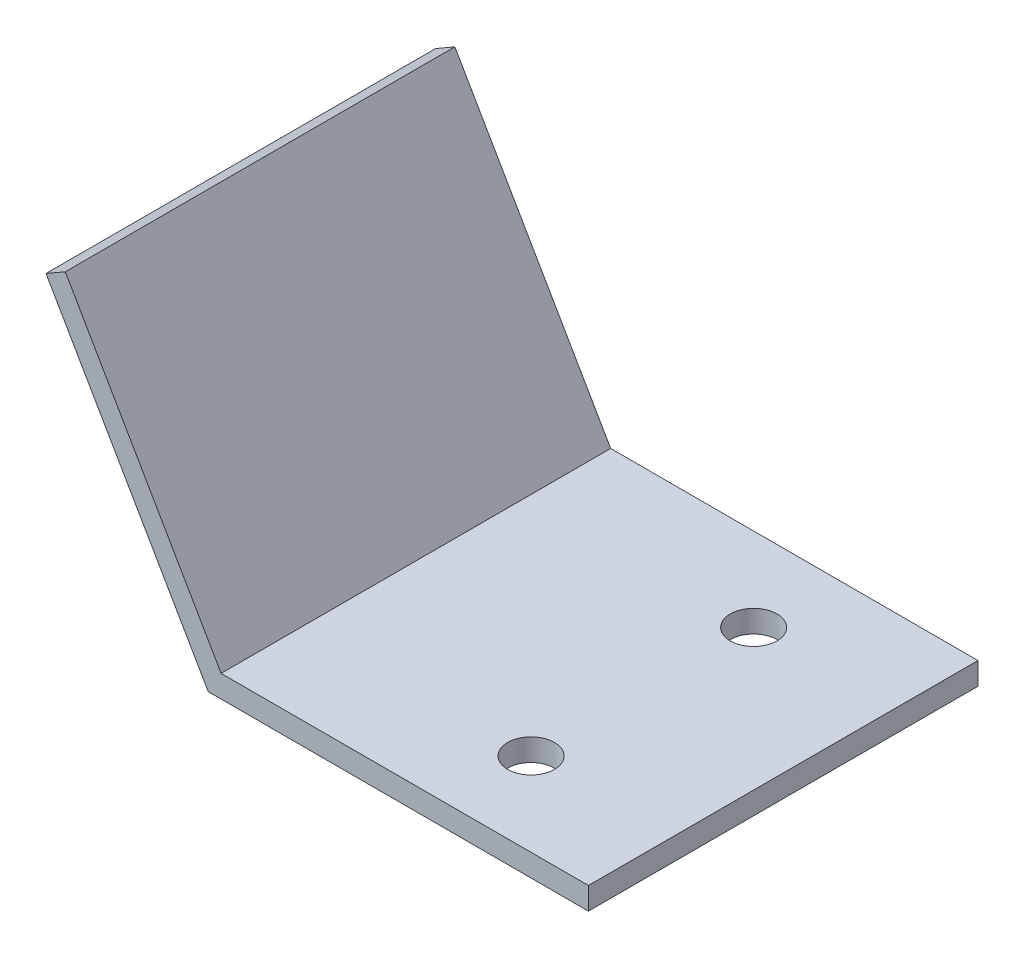
SolidWorks part; units mm, degrees
ref_plane "前视基准面" through (0, 0, 0) normal (0, 0, 1) x (1, 0, 0)
ref_plane "上视基准面" through (0, 0, 0) normal (0, 1, 0) x (1, 0, 0)
ref_plane "右视基准面" through (0, 0, 0) normal (1, 0, 0) x (0, 0, -1)
other "Configuration Table"
sketch "草图1" plane through (0, 0, 0) normal (0, 0, 1) x (1, 0, 0)
  line L0 (0, 0) -> (34.1547, 0)
  line L1 (34.1547, 0) -> (34.1547, 2)
  line L2 (34.1547, 2) -> (1.1547, 2)
  line L3 (1.1547, 2) -> (-12.8453, 26.2487)
  line L4 (-12.8453, 26.2487) -> (-14.5774, 25.2487)
  line L5 (-14.5774, 25.2487) -> (0, 0)
  dimension "D1" = 120
  dimension "D2" = 120
  dimension "D3" = 33
  dimension "D4" = 28
  dimension "D5" = 2
  dimension "D6" = 2
extrude "凸台-拉伸3" add sketch "草图1" along normal blind 35
sketch "草图3" plane through (0, 0, 0) normal (0, -1, 0) x (1, 0, 0)
  line L0 (0, 17.5) -> (34.1547, 17.5) construction
  line L1 (0, 35) -> (0, 0) construction
  line L2 (34.1547, 35) -> (34.1547, 0) construction
  circle A0 centre (21.5, 27.5) radius 2.1
  circle A1 centre (21.5, 7.5) radius 2.1
  dimension "D1" = 10
  dimension "D2" = 21.5
extrude "切除-拉伸1" cut sketch "草图3" against normal through all
sketch "草图4" plane through (0, 0, 0) normal (-0.866, -0.5, 0) x (0, 0, 1)
  line L0 (17.5, 0) -> (17.5, 29.1547) construction
  line L1 (35, 0) -> (0, 0) construction
  line L2 (35, 29.1547) -> (0, 29.1547) construction
  circle A0 centre (27.5, 15) radius 5
  circle A1 centre (7.5, 15) radius 5
  dimension "D1" = 10
  dimension "D2" = 15
extrude "切除-拉伸2" cut sketch "草图4" against normal blind 1.7
